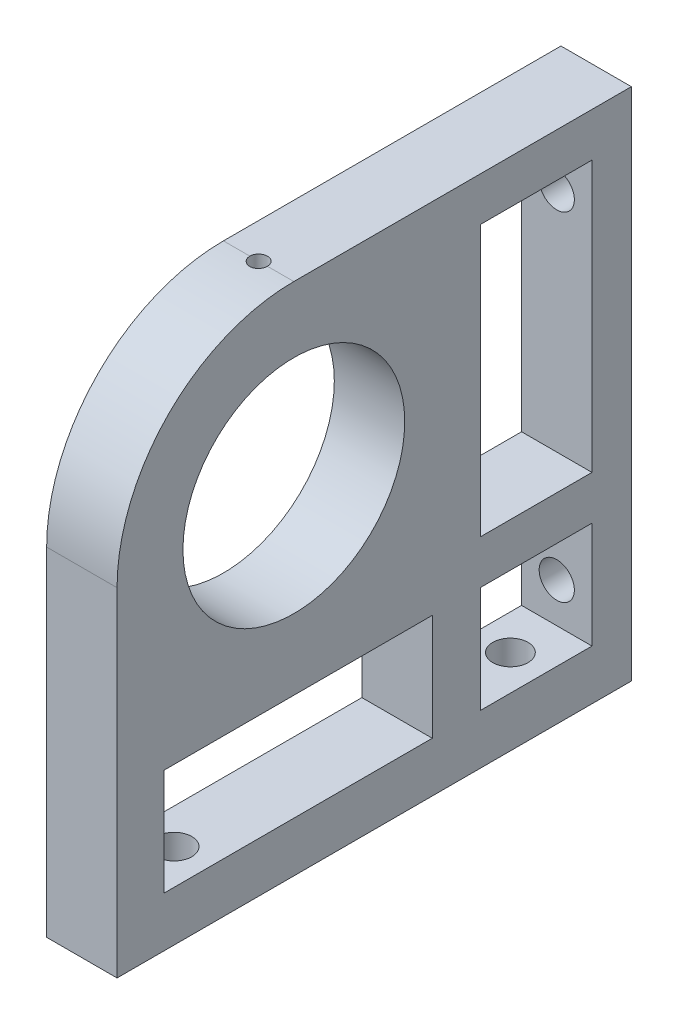
SolidWorks part; units mm, degrees
ref_plane "Front Plane" through (0, 0, 0) normal (0, 0, 1) x (1, 0, 0)
ref_plane "Top Plane" through (0, 0, 0) normal (0, 1, 0) x (1, 0, 0)
ref_plane "Right Plane" through (0, 0, 0) normal (1, 0, 0) x (0, 0, -1)
sketch "Sketch1" plane through (0, 0, 0) normal (1, 0, 0) x (0, 0, -1)
  line L11 (0, 31.8822) -> (31.8822, 31.8822)
  line L12 (31.8822, 31.8822) -> (60.8746, 31.8822)
  line L16 (60.8746, 31.8822) -> (60.8746, -60.96)
  line L17 (-31.8822, 0) -> (-31.8822, -60.96)
  line L18 (60.8746, -60.96) -> (-31.8822, -60.96)
  circle A1 centre (0, 0) radius 20
  arc A3 (0, 31.8822) -> (-31.8822, 0) centre (0, 0) ccw
extrude "Boss-Extrude1" add sketch "Sketch1" along normal blind 12.7
sketch "Sketch2" plane through (0, 0, 0) normal (0, 1, 0) x (1, 0, 0)
  circle A0 centre (6.35, 0) radius 1.5875
extrude "Cut-Extrude1" cut sketch "Sketch2" along normal through all
fillet "Fillet1" [suppressed] radius 2.54
mirror "Mirror1" [suppressed] about plane through (0, 0, 0) normal (0, 0, 1)
fillet "Fillet2" [suppressed] radius 5.08
sketch "Sketch4" plane through (0, 0, 0) normal (-1, 0, 0) x (0, 0, 1)
  line L4 (-53.7706, 23.9633) -> (-33.6922, 23.9633)
  line L5 (-33.6922, 23.9633) -> (-33.6922, -24.8177)
  line L6 (-24.9665, -32.7419) -> (23.4543, -32.7419)
  line L7 (23.4543, -32.7419) -> (23.4543, -51.9379)
  line L8 (23.4543, -51.9379) -> (-24.9665, -51.9379)
  line L9 (-53.7706, -51.9379) -> (-53.7706, -32.7419)
  line L10 (-33.6922, -32.7419) -> (-33.6922, -51.9379)
  line L11 (-24.9665, -51.9379) -> (-24.9665, -32.7419)
  line L12 (-33.6922, -51.9379) -> (-53.7706, -51.9379)
  line L13 (-33.6922, -32.7419) -> (-53.7706, -32.7419)
  line L14 (-33.6922, -24.8177) -> (-53.7706, -24.8177)
  line L15 (-53.7706, -24.8177) -> (-53.7706, 23.9633)
extrude "Cut-Extrude2" cut sketch "Sketch4" against normal blind 26.162
sketch "Sketch5" plane through (0, 0, -60.8746) normal (0, 0, -1) x (-1, 0, 0)
  circle A0 centre (-6.35, 16.187) radius 3.175
  circle A1 centre (-6.35, -44.7886) radius 3.175
extrude "Cut-Extrude3" cut sketch "Sketch5" against normal blind 11.43
sketch "Sketch6" plane through (0, -60.96, 0) normal (0, -1, 0) x (1, 0, 0)
  circle A0 centre (6.35, 15.24) radius 3.175
  circle A1 centre (6.35, -45.4106) radius 3.175
extrude "Cut-Extrude4" cut sketch "Sketch6" against normal blind 11.43
